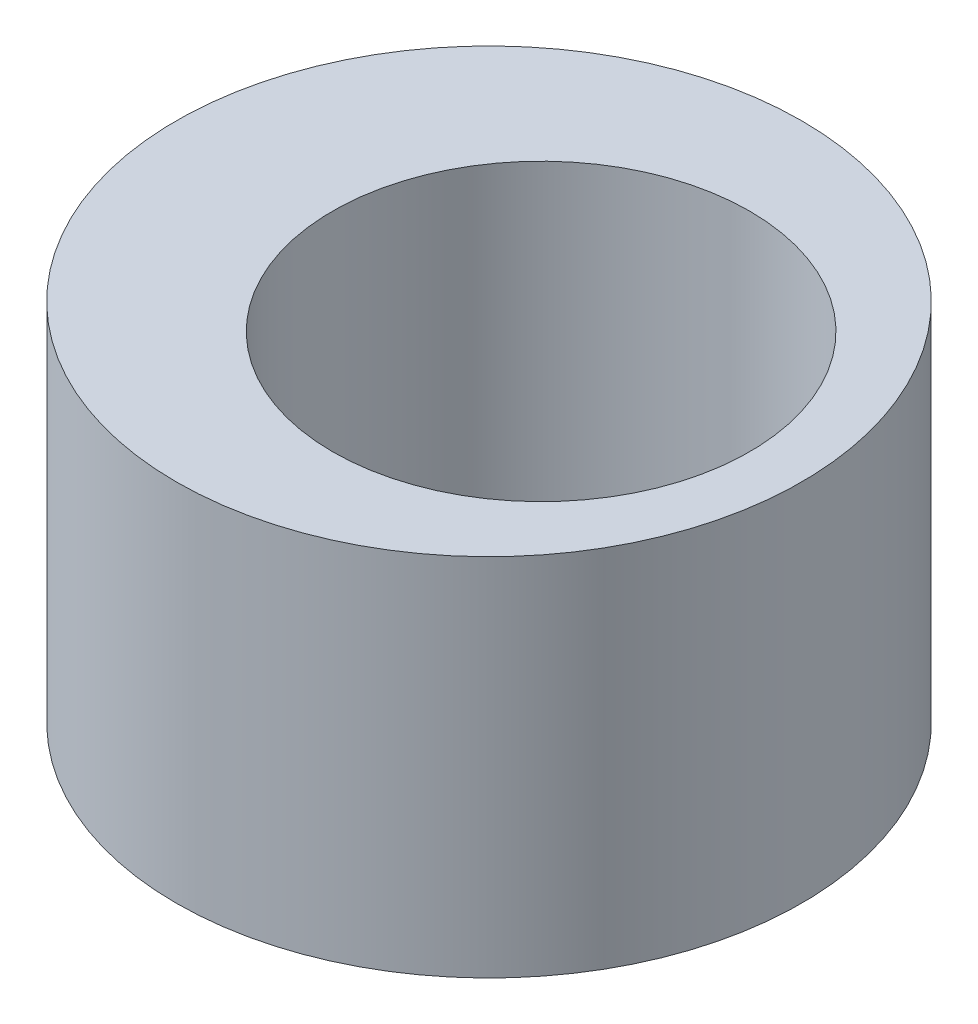
SolidWorks part; units mm, degrees
ref_plane "Front Plane" through (0, 0, 0) normal (0, 0, 1) x (1, 0, 0)
ref_plane "Top Plane" through (0, 0, 0) normal (0, 1, 0) x (1, 0, 0)
ref_plane "Right Plane" through (0, 0, 0) normal (1, 0, 0) x (0, 0, -1)
sketch "Sketch1" plane through (0, 0, 0) normal (0, 1, 0) x (1, 0, 0)
  line L0 (0, 0) -> (1, 0) construction
  circle A0 centre (0, 0) radius 6
  circle A1 centre (1, 0) radius 4
  dimension "D1" = 12
  dimension "D3" = 8
  dimension "D2" = 1
extrude "Boss-Extrude1" add sketch "Sketch1" along normal blind 7
